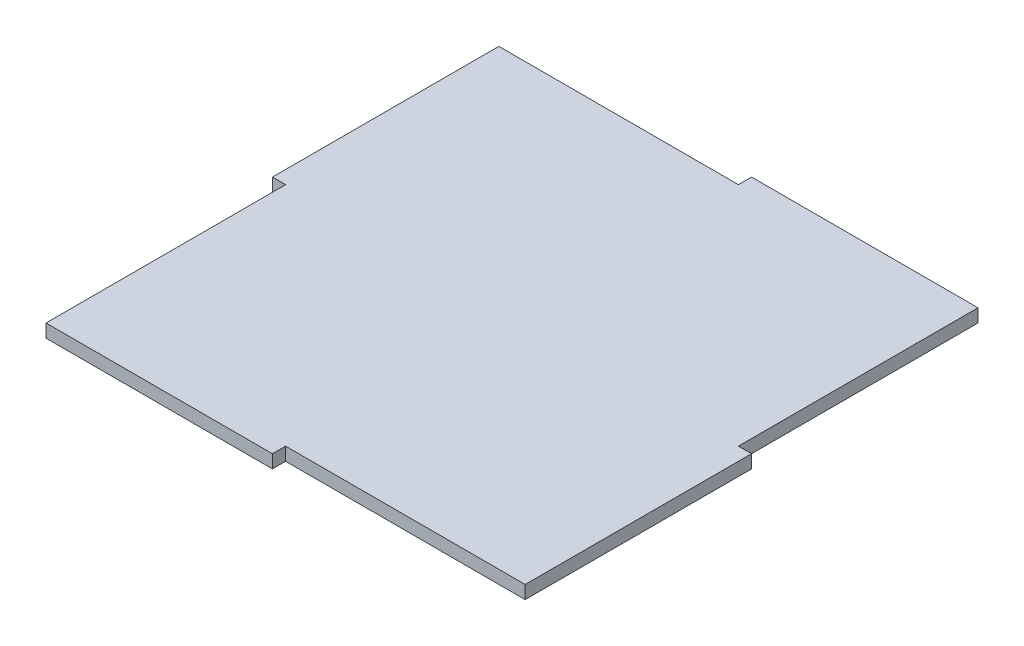
SolidWorks part; units mm, degrees
ref_plane "Přední rovina" through (0, 0, 0) normal (0, 0, 1) x (1, 0, 0)
ref_plane "Horní rovina" through (0, 0, 0) normal (0, 1, 0) x (1, 0, 0)
ref_plane "Pravá rovina" through (0, 0, 0) normal (1, 0, 0) x (0, 0, -1)
sketch "Skica1" plane through (0, 0, 0) normal (0, 1, 0) x (1, 0, 0)
  line L0 (41.3, 87.4) -> (82.6, 87.4)
  line L1 (-2.4, 85) -> (-2.4, 43.7)
  line L2 (0, 0) -> (41.3, 0)
  line L3 (85, 43.7) -> (85, 2.4)
  line L4 (-2.4, 43.7) -> (0, 43.7)
  line L5 (0, 43.7) -> (0, 0)
  line L6 (41.3, 0) -> (41.3, 2.4)
  line L7 (41.3, 2.4) -> (85, 2.4)
  line L8 (85, 43.7) -> (82.6, 43.7)
  line L9 (82.6, 43.7) -> (82.6, 87.4)
  line L10 (41.3, 87.4) -> (41.3, 85)
  line L11 (41.3, 85) -> (-2.4, 85)
  line L13 (85, 87.4) -> (-2.4, 87.4)
  line L14 (85, 87.4) -> (85, 0) construction
  line L15 (85, 0) -> (-2.4, 0)
  line L16 (-2.4, 87.4) -> (-2.4, 0)
  point P12 (41.3, 0)
  point P15 (41.3, 87.4)
  point P19 (-2.4, 43.7)
  point P20 (85, 43.7)
  dimension "D1" = 87.4
  dimension "D2" = 2.4
  dimension "D3" = 87.4
extrude "Přidat vysunutím1" add sketch "Skica1" along normal blind 2.4 contours L10 L11 L1 L4 L5 L2 L6 L7 L3 L8 L9 L0
